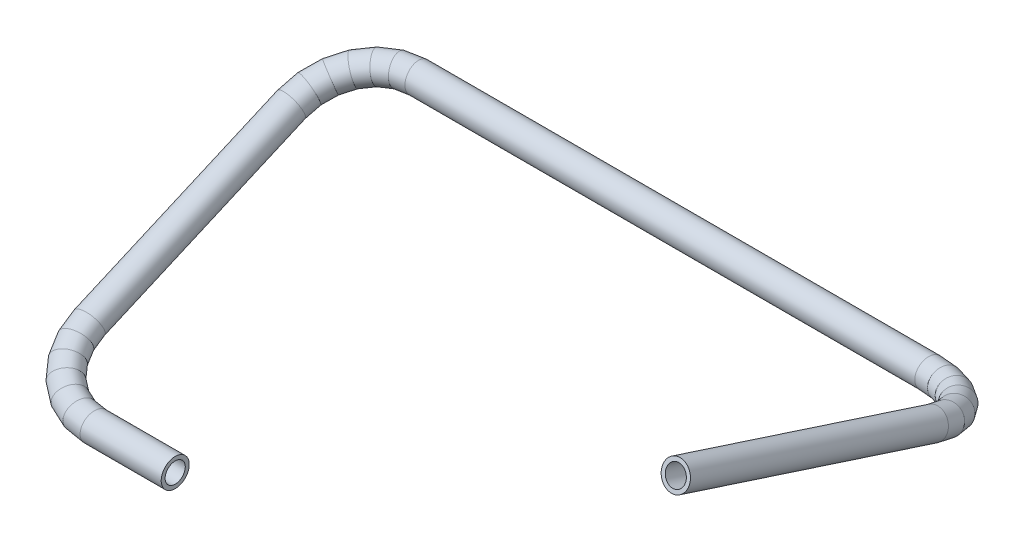
SolidWorks part; units mm, degrees
ref_plane "Front Plane" through (0, 0, 0) normal (0, 0, 1) x (1, 0, 0)
ref_plane "Top Plane" through (0, 0, 0) normal (0, 1, 0) x (1, 0, 0)
ref_plane "Right Plane" through (0, 0, 0) normal (1, 0, 0) x (0, 0, -1)
sketch3d "Path"
  line L0 (-2892.8928, -59.0885, -10.4189) -> (-2911.0928, -59.0885, -10.4189)
  line L1 (-2911.0928, -59.0885, -10.4189) -> (-2914.9751, -58.8845, -10.8875)
  line L2 (-2914.9751, -58.8845, -10.8875) -> (-2918.5928, -58.2864, -12.2615)
  line L3 (-2918.5928, -58.2864, -12.2615) -> (-2921.6994, -57.335, -14.4472)
  line L4 (-2921.6994, -57.335, -14.4472) -> (-2924.0832, -56.0951, -17.2957)
  line L5 (-2924.0832, -56.0951, -17.2957) -> (-2925.5817, -54.6513, -20.6127)
  line L6 (-2925.5817, -54.6513, -20.6127) -> (-2926.0928, -53.1018, -24.1724)
  line L7 (-2926.0928, -53.1018, -24.1724) -> (-2926.0928, -33.1802, -69.9394)
  line L8 (-2926.0928, -33.1802, -69.9394) -> (-2925.5817, -31.6307, -73.4991)
  line L9 (-2925.5817, -31.6307, -73.4991) -> (-2924.0832, -30.1868, -76.8162)
  line L10 (-2924.0832, -30.1868, -76.8162) -> (-2921.6994, -28.947, -79.6647)
  line L11 (-2921.6994, -28.947, -79.6647) -> (-2918.5928, -27.9956, -81.8503)
  line L12 (-2918.5928, -27.9956, -81.8503) -> (-2914.9751, -27.3975, -83.2243)
  line L13 (-2914.9751, -27.3975, -83.2243) -> (-2911.0928, -27.1935, -83.693)
  line L14 (-2911.0928, -27.1935, -83.693) -> (-2795.0928, -27.1935, -83.693)
  line L15 (-2795.0928, -27.1935, -83.693) -> (-2791.2105, -27.0356, -83.2069)
  line L16 (-2791.2105, -27.0356, -83.2069) -> (-2787.5928, -26.5725, -81.7817)
  line L17 (-2787.5928, -26.5725, -81.7817) -> (-2784.4862, -25.8359, -79.5146)
  line L18 (-2784.4862, -25.8359, -79.5146) -> (-2782.1024, -24.8759, -76.56)
  line L19 (-2782.1024, -24.8759, -76.56) -> (-2780.6039, -23.7579, -73.1194)
  line L20 (-2780.6039, -23.7579, -73.1194) -> (-2780.0928, -22.5582, -69.4271)
  line L21 (-2780.0928, -22.5582, -69.4271) -> (-2780.0928, -3.6155, -11.1274)
ref_plane "Start Plane" through (-2892.8928, 0, 0) normal (1, 0, 0) x (0, 0, -1)
sketch "Profile" plane through (-2892.8928, 0, 0) normal (1, 0, 0) x (0, 0, -1)
  circle A0 centre (10.4189, -59.0885) radius 3.175
  circle A1 centre (10.4189, -59.0885) radius 2.286
sweep "Tube" add profiles "Profile" path "Path"
